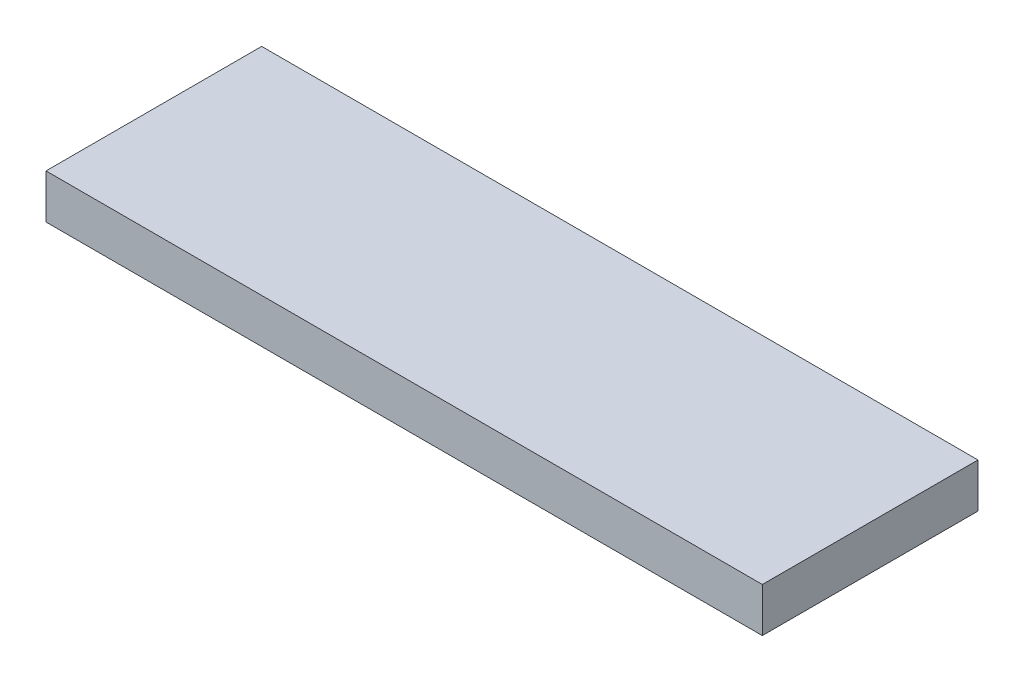
SolidWorks part; units mm, degrees
material "Pine"
ref_plane "Front Plane" through (0, 0, 0) normal (0, 0, 1) x (1, 0, 0)
ref_plane "Top Plane" through (0, 0, 0) normal (0, 1, 0) x (1, 0, 0)
ref_plane "Right Plane" through (0, 0, 0) normal (1, 0, 0) x (0, 0, -1)
sketch "Sketch1" plane through (0, 0, 0) normal (0, 1, 0) x (1, 0, 0)
  line L1 (-147.6375, 44.45) -> (147.6375, 44.45)
  line L2 (-147.6375, 44.45) -> (-147.6375, -44.45)
  line L3 (-147.6375, -44.45) -> (147.6375, -44.45)
  line L4 (147.6375, 44.45) -> (147.6375, -44.45)
  line L5 (-147.6375, 44.45) -> (147.6375, -44.45) construction
  line L6 (-147.6375, -44.45) -> (147.6375, 44.45) construction
  point P0 (0, 0)
  dimension "D1" = 295.275
  dimension "D2" = 88.9
extrude "Boss-Extrude1" add sketch "Sketch1" along normal blind 18.2562
